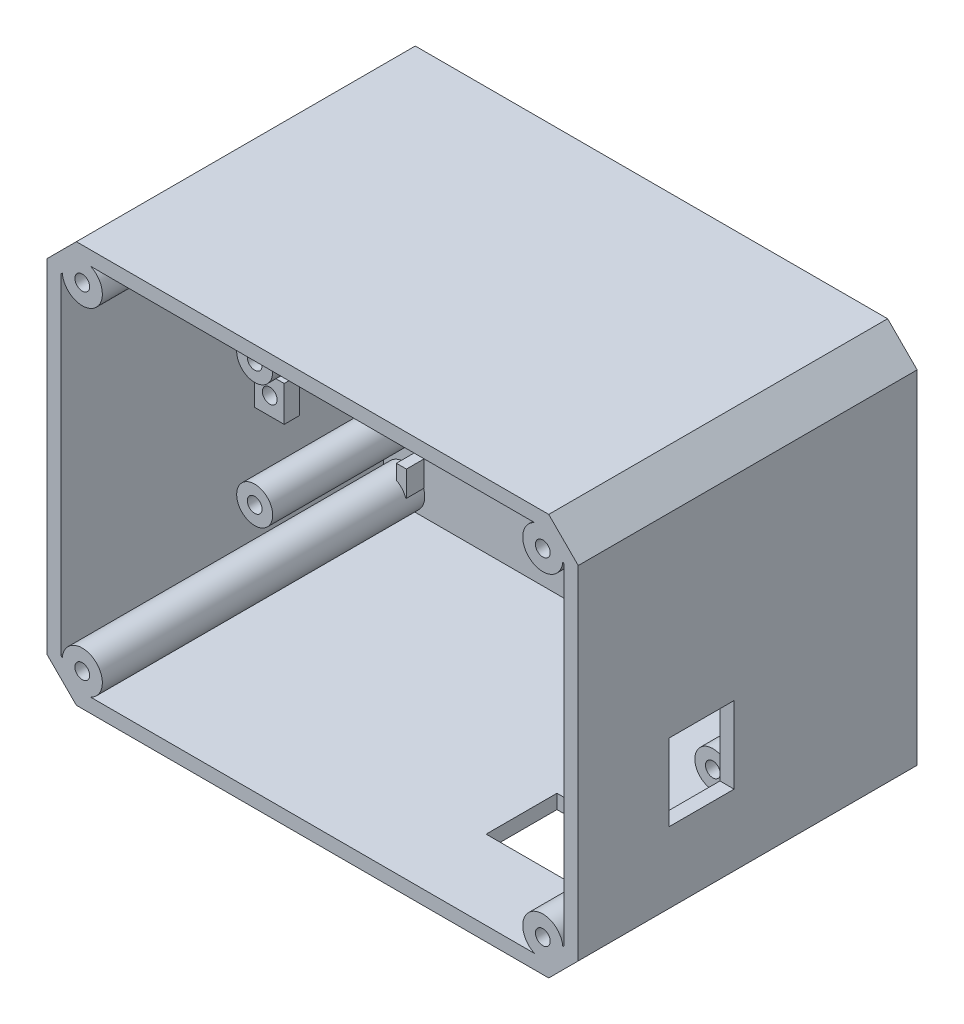
SolidWorks part; units mm, degrees
ref_plane "前视基准面" through (0, 0, 0) normal (0, 0, 1) x (1, 0, 0)
ref_plane "上视基准面" through (0, 0, 0) normal (0, 1, 0) x (1, 0, 0)
ref_plane "右视基准面" through (0, 0, 0) normal (1, 0, 0) x (0, 0, -1)
other "Configuration Table"
sketch "Floor - case mounting and battery strap holes profile" plane through (0, 0, 0) normal (0, 0, 1) x (1, 0, 0)
  line L0 (-40, -34) -> (40, -34)
  line L1 (40, -34) -> (45, -29)
  line L2 (45, -29) -> (45, 29)
  line L3 (45, 29) -> (40, 34)
  line L4 (40, 34) -> (-40, 34)
  line L5 (-40, 34) -> (-45, 29)
  line L6 (-45, 29) -> (-45, -29)
  line L7 (-45, -29) -> (-40, -34)
  line L8 (-0.1, -31.15) -> (5.1, -31.15)
  line L9 (5.1, -29.35) -> (-0.1, -29.35)
  line L10 (0, 5.2) -> (5, 5.2)
  line L11 (5, 7.2) -> (0, 7.2)
  circle A0 centre (-39, -8) radius 2.1
  circle A1 centre (39, -8) radius 2.1
  circle A2 centre (-39, 20) radius 2.1
  circle A3 centre (39, 20) radius 2.1
  arc A4 (5.1, -31.15) -> (5.1, -29.35) centre (5.1, -30.25) ccw
  arc A5 (-0.1, -29.35) -> (-0.1, -31.15) centre (-0.1, -30.25) ccw
  arc A6 (5, 5.2) -> (5, 7.2) centre (5, 6.2) ccw
  arc A7 (0, 7.2) -> (0, 5.2) centre (0, 6.2) ccw
extrude "Floor - case mounting and battery strap holes" add sketch "Floor - case mounting and battery strap holes profile" along normal blind 2.8
sketch "2.4 mm walls profile" plane through (0, 0, 0) normal (0, 0, 1) x (1, 0, 0)
  line L0 (-40, -34) -> (40, -34)
  line L1 (40, -34) -> (45, -29)
  line L2 (45, -29) -> (45, 29)
  line L3 (45, 29) -> (40, 34)
  line L4 (40, 34) -> (-40, 34)
  line L5 (-40, 34) -> (-45, 29)
  line L6 (-45, 29) -> (-45, -29)
  line L7 (-45, -29) -> (-40, -34)
  line L8 (-39, -31.6) -> (39, -31.6)
  line L9 (39, -31.6) -> (42.6, -28)
  line L10 (42.6, -28) -> (42.6, 28)
  line L11 (42.6, 28) -> (39, 31.6)
  line L12 (39, 31.6) -> (-39, 31.6)
  line L13 (-39, 31.6) -> (-42.6, 28)
  line L14 (-42.6, 28) -> (-42.6, -28)
  line L15 (-42.6, -28) -> (-39, -31.6)
extrude "2.4 mm walls" add sketch "2.4 mm walls profile" along normal blind 54.6 from offset 2.8
sketch "Lid posts - D2.5 pilots core profile" plane through (0, 0, 0) normal (0, 0, 1) x (1, 0, 0)
  circle A0 centre (-39, -28.5) radius 3.4
  circle A1 centre (39, -28.5) radius 3.4
  circle A2 centre (-39, 28.5) radius 3.4
  circle A3 centre (39, 28.5) radius 3.4
extrude "Lid posts - D2.5 pilots core" add sketch "Lid posts - D2.5 pilots core profile" along normal blind 46.6 from offset 2.8
sketch "Lid posts - D2.5 pilots profile" plane through (0, 0, 0) normal (0, 0, 1) x (1, 0, 0)
  circle A0 centre (-39, -28.5) radius 3.4
  circle A1 centre (39, -28.5) radius 3.4
  circle A2 centre (-39, 28.5) radius 3.4
  circle A3 centre (39, 28.5) radius 3.4
  circle A4 centre (-39, -28.5) radius 1.25
  circle A5 centre (39, -28.5) radius 1.25
  circle A6 centre (-39, 28.5) radius 1.25
  circle A7 centre (39, 28.5) radius 1.25
extrude "Lid posts - D2.5 pilots" add sketch "Lid posts - D2.5 pilots profile" along normal blind 8 from offset 49.4
sketch "Upper shelf posts - D2.5 pilots core profile" plane through (0, 0, 0) normal (0, 0, 1) x (1, 0, 0)
  circle A0 centre (-38.8, -18.5) radius 3.05
  circle A1 centre (38.8, -18.5) radius 3.05
  circle A2 centre (-38.8, 2.5) radius 3.05
  circle A3 centre (38.8, 2.5) radius 3.05
extrude "Upper shelf posts - D2.5 pilots core" add sketch "Upper shelf posts - D2.5 pilots core profile" along normal blind 19.6 from offset 2.8
sketch "Upper shelf posts - D2.5 pilots profile" plane through (0, 0, 0) normal (0, 0, 1) x (1, 0, 0)
  circle A0 centre (-38.8, -18.5) radius 3.05
  circle A1 centre (38.8, -18.5) radius 3.05
  circle A2 centre (-38.8, 2.5) radius 3.05
  circle A3 centre (38.8, 2.5) radius 3.05
  circle A4 centre (-38.8, -18.5) radius 1.25
  circle A5 centre (38.8, -18.5) radius 1.25
  circle A6 centre (-38.8, 2.5) radius 1.25
  circle A7 centre (38.8, 2.5) radius 1.25
extrude "Upper shelf posts - D2.5 pilots" add sketch "Upper shelf posts - D2.5 pilots profile" along normal blind 6 from offset 22.4
sketch "IIM sensor - two D1.65 pilots on 19 mm centers profile" plane through (0, 0, 0) normal (0, 0, 1) x (1, 0, 0)
  circle A0 centre (7, 28) radius 3
  circle A1 centre (26, 28) radius 3
  circle A2 centre (7, 28) radius 0.825
  circle A3 centre (26, 28) radius 0.825
extrude "IIM sensor - two D1.65 pilots on 19 mm centers" add sketch "IIM sensor - two D1.65 pilots on 19 mm centers profile" along normal blind 3.6 from offset 2.8
sketch "LC76G provisional D1.65 pilots profile" plane through (0, 0, 0) normal (0, 0, 1) x (1, 0, 0)
  circle A0 centre (-29.25, 8.3) radius 2.65
  circle A1 centre (-29.25, 28.8) radius 2.65
  circle A2 centre (-29.25, 8.3) radius 0.825
  circle A3 centre (-29.25, 28.8) radius 0.825
extrude "LC76G provisional D1.65 pilots" add sketch "LC76G provisional D1.65 pilots profile" along normal blind 3.6 from offset 2.8
sketch "GNSS un-drilled support profile" plane through (0, 0, 0) normal (0, 0, 1) x (1, 0, 0)
  line L0 (-5.6, 23.4) -> (-1.7, 23.4)
  line L1 (-1.7, 23.4) -> (-1.7, 28.2)
  line L2 (-1.7, 28.2) -> (-5.6, 28.2)
  line L3 (-5.6, 28.2) -> (-5.6, 23.4)
extrude "GNSS un-drilled support" add sketch "GNSS un-drilled support profile" along normal blind 3.6 from offset 2.8
sketch "Battery locating end stops profile" plane through (0, 0, 0) normal (0, 0, 1) x (1, 0, 0)
  line L0 (-37.4, -27.3) -> (-35.7, -27.3)
  line L1 (-35.7, -27.3) -> (-35.7, -23)
  line L2 (-35.7, -23) -> (-37.4, -23)
  line L3 (-37.4, -23) -> (-37.4, -27.3)
  line L4 (33.7, -28) -> (36.2, -28)
  line L5 (36.2, -28) -> (36.2, -25.2)
  line L6 (36.2, -25.2) -> (33.7, -25.2)
  line L7 (33.7, -25.2) -> (33.7, -28)
extrude "Battery locating end stops" add sketch "Battery locating end stops profile" along normal blind 3 from offset 2.8
sketch "Power plate guide seats profile" plane through (0, 0, 0) normal (0, 0, 1) x (1, 0, 0)
  line L0 (-36.2, 26.8) -> (-30.1, 26.8)
  line L1 (-30.1, 26.8) -> (-30.1, 32.1)
  line L2 (-30.1, 32.1) -> (-36.2, 32.1)
  line L3 (-36.2, 32.1) -> (-36.2, 26.8)
  line L4 (30.1, 26.8) -> (36.2, 26.8)
  line L5 (36.2, 26.8) -> (36.2, 32.1)
  line L6 (36.2, 32.1) -> (30.1, 32.1)
  line L7 (30.1, 32.1) -> (30.1, 26.8)
extrude "Power plate guide seats" add sketch "Power plate guide seats profile" along normal blind 2.4 from offset 9.4
sketch "Power plate rear guide channels profile" plane through (0, 0, 0) normal (0, 0, 1) x (1, 0, 0)
  line L0 (30.1, 26.8) -> (36.2, 26.8)
  line L1 (36.2, 26.8) -> (36.2, 32.1)
  line L2 (36.2, 32.1) -> (32.4, 32.1)
  line L3 (32.4, 32.1) -> (32.4, 27.75)
  line L4 (32.4, 27.75) -> (30.1, 27.75)
  line L5 (30.1, 27.75) -> (30.1, 26.8)
  line L6 (-30.1, 26.8) -> (-36.2, 26.8)
  line L7 (-36.2, 26.8) -> (-36.2, 32.1)
  line L8 (-36.2, 32.1) -> (-32.4, 32.1)
  line L9 (-32.4, 32.1) -> (-32.4, 27.75)
  line L10 (-32.4, 27.75) -> (-30.1, 27.75)
  line L11 (-30.1, 27.75) -> (-30.1, 26.8)
extrude "Power plate rear guide channels" add sketch "Power plate rear guide channels profile" along normal blind 18.3 from offset 11.8
sketch "Power plate guide ends - keeper washer pilots profile" plane through (0, 0, 0) normal (0, 0, 1) x (1, 0, 0)
  line L0 (30.1, 26.8) -> (36.2, 26.8)
  line L1 (36.2, 26.8) -> (36.2, 32.1)
  line L2 (36.2, 32.1) -> (32.4, 32.1)
  line L3 (32.4, 32.1) -> (32.4, 27.75)
  line L4 (32.4, 27.75) -> (30.1, 27.75)
  line L5 (30.1, 27.75) -> (30.1, 26.8)
  line L6 (-30.1, 26.8) -> (-36.2, 26.8)
  line L7 (-36.2, 26.8) -> (-36.2, 32.1)
  line L8 (-36.2, 32.1) -> (-32.4, 32.1)
  line L9 (-32.4, 32.1) -> (-32.4, 27.75)
  line L10 (-32.4, 27.75) -> (-30.1, 27.75)
  line L11 (-30.1, 27.75) -> (-30.1, 26.8)
  circle A0 centre (-34.1, 29.4) radius 1.05
  circle A1 centre (34.1, 29.4) radius 1.05
extrude "Power plate guide ends - keeper washer pilots" add sketch "Power plate guide ends - keeper washer pilots profile" along normal blind 4.5 from offset 30.1
sketch "Vertical cable ties - D2.5 guide eyes profile" plane through (0, 0, 0) normal (0, 0, 1) x (1, 0, 0)
  line L0 (-42.8, -8) -> (-37.6, -8)
  line L1 (-37.6, -8) -> (-37.6, -2)
  line L2 (-37.6, -2) -> (-42.8, -2)
  line L3 (-42.8, -2) -> (-42.8, -8)
  circle A0 centre (-40.05, -5) radius 1.25
extrude "Vertical cable ties - D2.5 guide eyes" add sketch "Vertical cable ties - D2.5 guide eyes profile" along normal blind 2.6 from offset 11
sketch "Upper cable tie eye profile" plane through (0, 0, 0) normal (0, 0, 1) x (1, 0, 0)
  line L0 (-42.8, -8) -> (-37.6, -8)
  line L1 (-37.6, -8) -> (-37.6, -2)
  line L2 (-37.6, -2) -> (-42.8, -2)
  line L3 (-42.8, -2) -> (-42.8, -8)
  circle A0 centre (-40.05, -5) radius 1.25
extrude "Upper cable tie eye" add sketch "Upper cable tie eye profile" along normal blind 2.6 from offset 22
sketch "USB access reserve 13 x 11 profile" plane through (0, 0, 0) normal (0, 0, 1) x (1, 0, 0)
  line L0 (42, -17) -> (45.4, -17)
  line L1 (45.4, -17) -> (45.4, -4)
  line L2 (45.4, -4) -> (42, -4)
  line L3 (42, -4) -> (42, -17)
extrude "USB access reserve 13 x 11" cut sketch "USB access reserve 13 x 11 profile" against normal blind 11 from offset 42
sketch "LoRa antenna reserve 16 x 12 profile" plane through (0, 0, 0) normal (0, 0, 1) x (1, 0, 0)
  line L0 (16, -34.4) -> (32, -34.4)
  line L1 (32, -34.4) -> (32, -31)
  line L2 (32, -31) -> (16, -31)
  line L3 (16, -31) -> (16, -34.4)
extrude "LoRa antenna reserve 16 x 12" cut sketch "LoRa antenna reserve 16 x 12 profile" against normal blind 12 from offset 44
